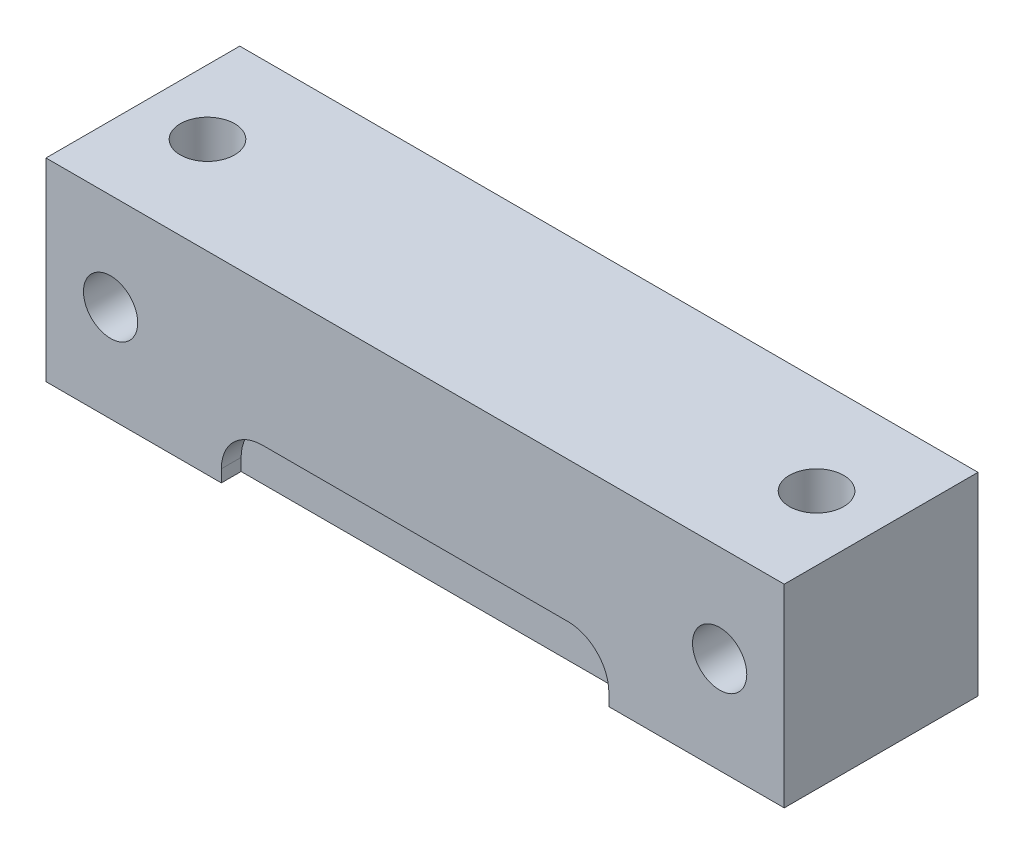
SolidWorks part; units mm, degrees
ref_plane "Front Plane" through (0, 0, 0) normal (0, 0, 1) x (1, 0, 0)
ref_plane "Top Plane" through (0, 0, 0) normal (0, 1, 0) x (1, 0, 0)
ref_plane "Right Plane" through (0, 0, 0) normal (1, 0, 0) x (0, 0, -1)
sketch "Sketch1" plane through (0, 0, 0) normal (1, 0, 0) x (0, 0, -1)
  line L1 (-7.5, -7.5) -> (7.5, -7.5)
  line L2 (-7.5, -7.5) -> (-7.5, 7.5)
  line L3 (-7.5, 7.5) -> (7.5, 7.5)
  line L4 (7.5, -7.5) -> (7.5, 7.5)
  line L5 (-7.5, -7.5) -> (7.5, 7.5) construction
  line L6 (-7.5, 7.5) -> (7.5, -7.5) construction
  point P0 (0, 0)
  dimension "D1" = 15
  dimension "D2" = 15
extrude "Boss-Extrude1" add sketch "Sketch1" along normal blind 57.15
sketch "Sketch2" plane through (0, 0, 7.5) normal (0, 0, 1) x (1, 0, 0)
  line L2 (57.15, -7.5) -> (0, -7.5) construction
  line L3 (0, 7.5) -> (0, -7.5) construction
  line L4 (57.15, 7.5) -> (57.15, -7.5) construction
  point P0 (5, 0)
  point P1 (52.15, 0)
  dimension "D1" = 7.5
  dimension "D2" = 5
  dimension "D3" = 5
  dimension "D4" = 7.5
hole_wizard "M5x0.8 Tapped Hole1" positions "Sketch5" profile "Sketch6" tap size "M5x0.8" standard "ANSI Metric" end condition through all
sketch "Sketch5" plane through (0, 0, 7.5) normal (0, 0, 1) x (1, 0, 0)
  point P0 (5, 0)
  point P3 (52.15, 0)
sketch "Sketch6" plane through (5, 0, 7.5) normal (1, 0, 0) x (0, -1, 0)
  line L0 (0, 0) -> (0, 15)
  line L1 (0, 15) -> (2.1, 15)
  line L2 (2.1, 15) -> (2.1, 0)
  line L5 (2.1, 0) -> (0, 0)
  line L11 (0, -6.35) -> (0, 107.95) construction
  dimension "Thru Tap Drill Dia." = 4.2
  dimension "Thru Tap Drill Depth" = 15
cosmetic thread "Hole Thread1" parameters "D2"=5
cosmetic thread "Hole Thread2" parameters "D2"=5
sketch "Sketch7" plane through (0, -7.5, 0) normal (0, -1, 0) x (1, 0, 0)
  line L0 (0, 7.5) -> (0, -7.5) construction
  line L1 (57.15, 7.5) -> (57.15, -7.5) construction
  line L2 (57.15, -7.5) -> (0, -7.5) construction
  point P0 (5, 0)
  point P1 (52.15, 0)
  dimension "D1" = 5
  dimension "D2" = 5
  dimension "D3" = 7.5
  dimension "D4" = 7.5
hole_wizard "M5x0.8 Tapped Hole2" positions "Sketch9" profile "Sketch8" tap size "M5x0.8" standard "ANSI Metric" end condition through all
sketch "Sketch9" plane through (0, -7.5, 0) normal (0, -1, 0) x (-1, 0, 0)
  point P0 (-5, 0)
  point P3 (-52.15, 0)
cosmetic thread "Hole Thread3" parameters "D2"=5
cosmetic thread "Hole Thread4" parameters "D2"=5
sketch "Sketch8" plane through (5, -7.5, 0) normal (1, 0, 0) x (0, 0, -1)
  line L0 (0, 0) -> (0, 15)
  line L1 (0, 15) -> (2.1, 15)
  line L2 (2.1, 15) -> (2.1, 0)
  line L5 (2.1, 0) -> (0, 0)
  line L11 (0, -6.35) -> (0, 107.95) construction
  dimension "Thru Tap Drill Dia." = 4.2
  dimension "Thru Tap Drill Depth" = 15
sketch "Sketch10" plane through (0, -7.5, 0) normal (0, -1, 0) x (1, 0, 0)
  line L0 (57.15, -7.5) -> (0, -7.5) construction
  line L1 (11.3668, -12.3376) -> (45.7832, -12.3376)
  line L2 (11.3668, -12.3376) -> (11.3668, -2.6624)
  line L3 (11.3668, -2.6624) -> (45.7832, -2.6624)
  line L4 (45.7832, -12.3376) -> (45.7832, -2.6624)
  line L5 (11.3668, -12.3376) -> (45.7832, -2.6624) construction
  line L6 (11.3668, -2.6624) -> (45.7832, -12.3376) construction
  point P0 (28.575, -7.5)
extrude "Cut-Extrude1" [suppressed] cut sketch "Sketch10" against normal blind 2
fillet "Fillet1" [suppressed] radius 3.175
sketch "Sketch12" plane through (0, 0, 7.5) normal (0, 0, 1) x (1, 0, 0)
  line L0 (57.15, -7.5) -> (0, -7.5) construction
  line L1 (13.575, -11.6231) -> (43.575, -11.6231)
  line L2 (13.575, -11.6231) -> (13.575, -3.3769)
  line L3 (13.575, -3.3769) -> (43.575, -3.3769)
  line L4 (43.575, -11.6231) -> (43.575, -3.3769)
  line L5 (13.575, -11.6231) -> (43.575, -3.3769) construction
  line L6 (13.575, -3.3769) -> (43.575, -11.6231) construction
  point P0 (28.575, -7.5)
  dimension "D1" = 28.575
  dimension "D2" = 30
extrude "Cut-Extrude2" cut sketch "Sketch12" against normal blind 1.53
fillet "Fillet2" radius 3.175 2 edges at (43.575, -3.3769, 6.735) (13.575, -3.3769, 6.735)
